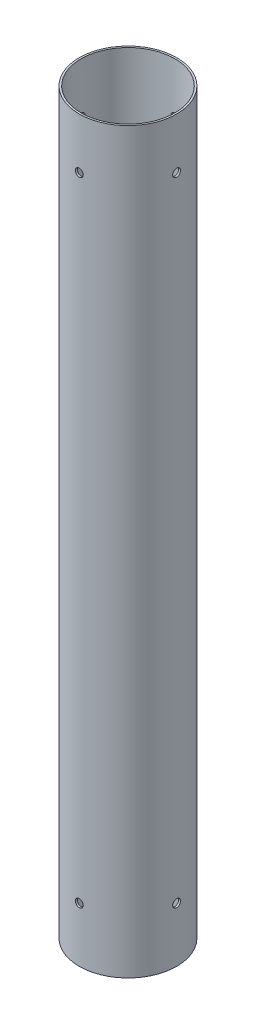
SolidWorks part; units mm, degrees
material "S-Glass Fiber"
ref_plane "Front Plane" through (0, 0, 0) normal (0, 0, 1) x (1, 0, 0)
ref_plane "Top Plane" through (0, 0, 0) normal (0, 1, 0) x (1, 0, 0)
ref_plane "Right Plane" through (0, 0, 0) normal (1, 0, 0) x (0, 0, -1)
sketch "Sketch4" plane through (0, 0, 0) normal (0, 1, 0) x (1, 0, 0)
  circle A0 centre (0, 0) radius 39.6
  circle A1 centre (0, 0) radius 38.1
  dimension "D1" = 79.2
  dimension "D2" = 76.2
extrude "Boss-Extrude2" add sketch "Sketch4" along normal blind 599.44
sketch "Sketch5" plane through (0, 0, 0) normal (1, 0, 0) x (0, 0, -1)
  line L0 (-39.6, 0) -> (39.6, 0) construction
  circle A0 centre (0, 44.45) radius 3.175
  dimension "D2" = 6.35
  dimension "D1" = 44.45
extrude "Cut-Extrude1" cut sketch "Sketch5" against normal through all
pattern_circular "CirPattern1" count 4 over 360 about axis through (0, 599.44, 0) along (0, -1, 0) of "Cut-Extrude1"
sketch "Sketch6" plane through (0, 0, 0) normal (1, 0, 0) x (0, 0, -1)
  line L0 (39.6, 599.44) -> (-39.6, 599.44) construction
  circle A0 centre (0, 558.165) radius 3.175
  dimension "D2" = 6.35
  dimension "D1" = 41.275
extrude "Cut-Extrude2" cut sketch "Sketch6" along normal through all
pattern_circular "CirPattern2" count 4 over 360 about axis through (0, 599.44, 0) along (0, -1, 0) of "Cut-Extrude2"
